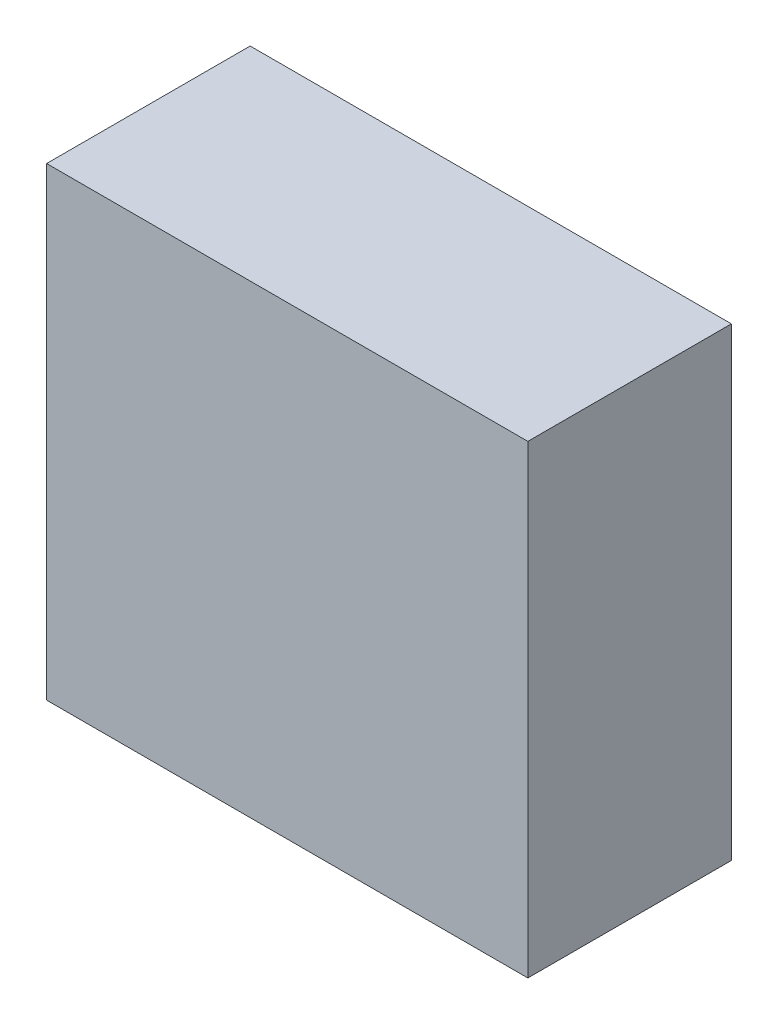
SolidWorks part; units mm, degrees
ref_plane "Front Plane" through (0, 0, 0) normal (0, 0, 1) x (1, 0, 0)
ref_plane "Top Plane" through (0, 0, 0) normal (0, 1, 0) x (1, 0, 0)
ref_plane "Right Plane" through (0, 0, 0) normal (1, 0, 0) x (0, 0, -1)
ref_plane "PZ17" through (0, 17, 0) normal (0, 1, 0) x (1, 0, 0)
sketch "Sketch1" plane through (0, 17, 0) normal (0, 1, 0) x (1, 0, 0)
  line L0 (-14.6, 30.65) -> (14.6, 30.65)
  line L1 (14.6, 30.65) -> (14.6, 43)
  line L2 (14.6, 43) -> (-14.6, 43)
  line L3 (-14.6, 43) -> (-14.6, 30.65)
extrude "Camera Case" add sketch "Sketch1" along normal blind 28.2
